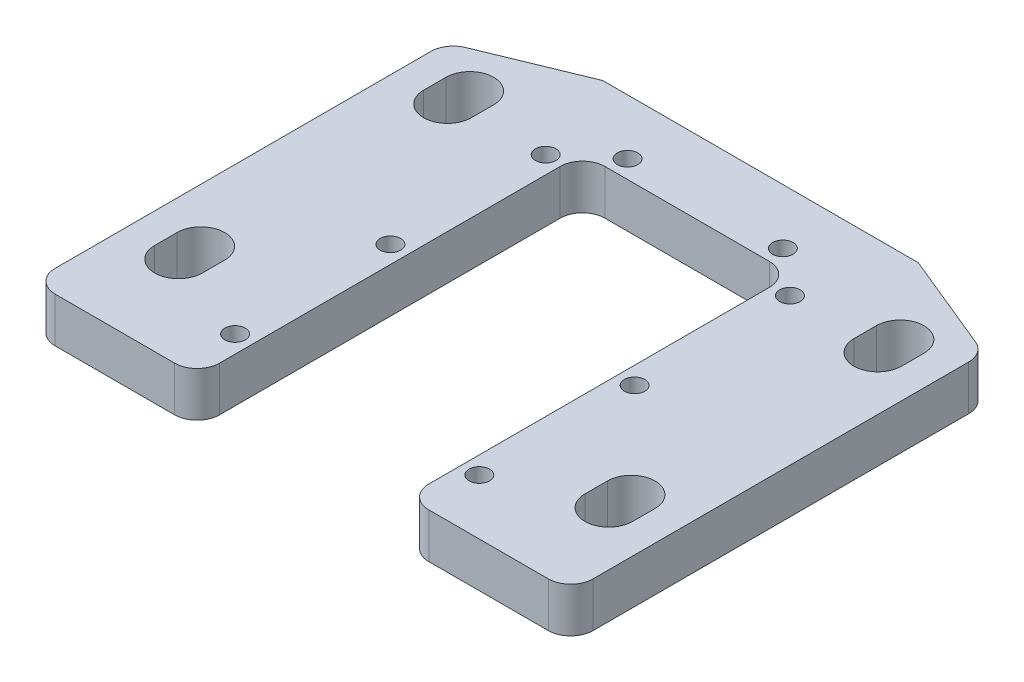
SolidWorks part; units mm, degrees
ref_plane "Front Plane" through (0, 0, 0) normal (0, 0, 1) x (1, 0, 0)
ref_plane "Top Plane" through (0, 0, 0) normal (0, 1, 0) x (1, 0, 0)
ref_plane "Right Plane" through (0, 0, 0) normal (1, 0, 0) x (0, 0, -1)
sketch "Sketch1" plane through (0, 0, 0) normal (0, 1, 0) x (1, 0, 0)
  line L1 (-38.1, 38.1) -> (38.1, 38.1)
  line L2 (-38.1, 38.1) -> (-38.1, -38.1)
  line L3 (-38.1, -38.1) -> (38.1, -38.1)
  line L4 (38.1, 38.1) -> (38.1, -38.1)
  line L5 (-38.1, 38.1) -> (38.1, -38.1) construction
  line L6 (-38.1, -38.1) -> (38.1, 38.1) construction
  point P0 (0, 0)
  dimension "D1" = 76.2
  dimension "D2" = 76.2
extrude "Boss-Extrude1" add sketch "Sketch1" along normal mid plane 6.35
sketch "Sketch2" plane through (0, 3.175, 0) normal (0, 1, 0) x (1, 0, 0)
  line L1 (-14.8273, 27.305) -> (14.8272, 27.305)
  line L2 (-14.8273, 27.305) -> (-14.8272, -27.305)
  line L3 (-14.8272, -27.305) -> (14.8273, -27.305)
  line L4 (14.8272, 27.305) -> (14.8273, -27.305)
  line L5 (-14.8273, 27.305) -> (14.8273, -27.305) construction
  line L6 (-14.8272, -27.305) -> (14.8272, 27.305) construction
  point P0 (0, 0)
  dimension "D1" = 29.6545
  dimension "D2" = 54.61
extrude "Cut-Extrude1" cut sketch "Sketch2" against normal through all
hole_wizard "M2.5 Clearance Hole1" positions "Sketch3" profile "Sketch4" hole size "M2.5" standard "ANSI Metric" end condition through all
sketch "Sketch3" plane through (0, 3.175, 0) normal (0, 1, 0) x (1, 0, 0)
  point P0 (-17.3, 24.551)
  point P3 (-11, 29.851)
  point P6 (-17.3, 2.551)
  point P9 (-17.3, -19.449)
sketch "Sketch4" plane through (-17.3, 3.175, -24.551) normal (1, 0, 0) x (0, 0, 1)
  line L0 (0, 0) -> (0, 6.35)
  line L1 (0, 6.35) -> (1.45, 6.35)
  line L2 (1.45, 6.35) -> (1.45, 0)
  line L5 (1.45, 0) -> (0, 0)
  line L11 (0, -6.35) -> (0, 107.95) construction
  dimension "Thru Hole Dia." = 2.9
  dimension "Thru Hole Depth" = 6.35
sketch "Sketch8" plane through (0, 3.175, 0) normal (0, 1, 0) x (1, 0, 0)
  line L0 (-30.48, -14.2875) -> (-30.48, -11.1125) construction
  line L1 (-33.8582, -14.2875) -> (-33.8582, -11.1125)
  line L2 (-27.1018, -14.2875) -> (-27.1018, -11.1125)
  line L3 (-30.48, 23.8125) -> (-30.48, 26.9875) construction
  line L4 (-33.8582, 23.8125) -> (-33.8582, 26.9875)
  line L5 (-27.1018, 23.8125) -> (-27.1018, 26.9875)
  line L6 (-38.1, -38.1) -> (38.1, -38.1) construction
  line L7 (-38.1, 38.1) -> (-38.1, -38.1) construction
  arc A0 (-33.8582, -14.2875) -> (-27.1018, -14.2875) centre (-30.48, -14.2875) ccw
  arc A1 (-27.1018, -11.1125) -> (-33.8582, -11.1125) centre (-30.48, -11.1125) ccw
  arc A2 (-33.8582, 23.8125) -> (-27.1018, 23.8125) centre (-30.48, 23.8125) ccw
  arc A3 (-27.1018, 26.9875) -> (-33.8582, 26.9875) centre (-30.48, 26.9875) ccw
  point P2 (-30.48, -12.7)
  point P7 (-30.48, 25.4)
  dimension "D5" = 3.3782
  dimension "D1" = 38.1
  dimension "D2" = 25.4
  dimension "D3" = 7.62
  dimension "D4" = 3.175
extrude "Cut-Extrude2" cut sketch "Sketch8" against normal through all
mirror "Mirror1" about plane through (0, 0, 0) normal (1, 0, 0) of "Cut-Extrude2", "M2.5 Clearance Hole1"
sketch "Sketch9" plane through (0, 3.175, 0) normal (0, 1, 0) x (1, 0, 0)
  line L0 (-14.8272, -27.305) -> (14.8273, -27.305) construction
  line L1 (-38.1, -27.305) -> (38.1, -27.305)
  line L2 (-38.1, -27.305) -> (-38.1, -38.1)
  line L3 (-38.1, -38.1) -> (38.1, -38.1)
  line L4 (38.1, -27.305) -> (38.1, -38.1)
  line L5 (-38.1, -27.305) -> (38.1, -38.1) construction
  line L6 (-38.1, -38.1) -> (38.1, -27.305) construction
  line L8 (38.1, 37.69) -> (-38.1, 37.69)
  line L9 (38.1, 37.69) -> (38.1, 38.1)
  line L10 (38.1, 38.1) -> (-38.1, 38.1)
  line L11 (-38.1, 37.69) -> (-38.1, 38.1)
  line L12 (38.1, 37.69) -> (-38.1, 38.1) construction
  line L13 (38.1, 38.1) -> (-38.1, 37.69) construction
  point P0 (0, -32.7025)
  point P6 (0, 37.895)
  dimension "D1" = 0.41
extrude "Cut-Extrude3" cut sketch "Sketch9" against normal through all
sketch "Sketch13" plane through (0, -3.175, 0) normal (0, -1, 0) x (1, 0, 0)
  line L0 (-38.1, -31.213) -> (-22.352, -37.69)
  line L1 (-38.1, -37.69) -> (-38.1, 27.305) construction
  line L2 (-38.1, -37.69) -> (38.1, -37.69) construction
  line L3 (-22.352, -37.69) -> (-38.1, -37.69)
  line L4 (-38.1, -37.69) -> (-38.1, -31.213)
  dimension "D1" = 6.477
  dimension "D2" = 15.748
extrude "Cut-Extrude4" cut sketch "Sketch13" against normal through all
mirror "Mirror3" about plane through (0, 0, 0) normal (1, 0, 0) of "Cut-Extrude4"
fillet "Fillet1" radius 3.175 8 edges at (14.8272, 0, 27.305) (-14.8272, 0, 27.305) (38.1, 0, 27.305) (-38.1, 0, 27.305) (14.8272, 0, -27.305) (-14.8273, 0, -27.305) (-38.1, 0, -31.213) (38.1, 0, -31.213)
mirror "Mirror2" [suppressed] about plane through (0, 0, 0) normal (1, 0, 0)
sketch "Sketch10" [suppressed] plane through (0, 0, -38.1) normal (0, 0, -1) x (-1, 0, 0)
  line L4 (-25.4, -3.175) -> (25.4, -3.175)
  line L5 (25.4, -3.175) -> (25.4, 3.175)
  line L6 (25.4, 3.175) -> (-25.4, 3.175)
  line L7 (-25.4, 3.175) -> (-25.4, -3.175)
  line L8 (-25.4, -3.175) -> (25.4, -3.175)
  line L9 (25.4, -3.175) -> (25.4, 3.175)
  line L10 (25.4, 3.175) -> (-25.4, 3.175)
  line L11 (-25.4, 3.175) -> (-25.4, -3.175)
  dimension "D1" = 0
extrude "Boss-Extrude2" [suppressed] add sketch "Sketch10" along normal mid plane 12.7
hole_wizard "#10 Clearance Hole1" [suppressed] positions "Sketch11" profile "Sketch12" hole size "#10" standard "ANSI Inch"
sketch "Sketch11" plane through (0, 3.175, 0) normal (0, 1, 0) x (1, 0, 0)
  line L0 (-19.05, 38.1) -> (19.05, 38.1)
  line L3 (-25.4, 44.45) -> (25.4, 44.45) construction
  point P0 (-19.05, 38.1)
  point P2 (19.05, 38.1)
  point P9 (0, 38.1)
  dimension "D1" = 6.35
  dimension "D2" = 38.1
sketch "Sketch12" plane through (-19.05, 3.175, -38.1) normal (1, 0, 0) x (0, 0, 1)
  line L0 (0, 0) -> (0, 14.2338)
  line L1 (0, 14.2338) -> (2.5527, 12.7)
  line L2 (2.5527, 12.7) -> (2.5527, 0)
  line L5 (2.5527, 0) -> (0, 0)
  line L10 (0, 14.2338) -> (-2.5527, 12.7) construction
  line L11 (0, -6.35) -> (0, 107.95) construction
  dimension "Hole Dia." = 5.1054
  dimension "Hole Depth" = 12.7
  dimension "Drill Angle" = 118
